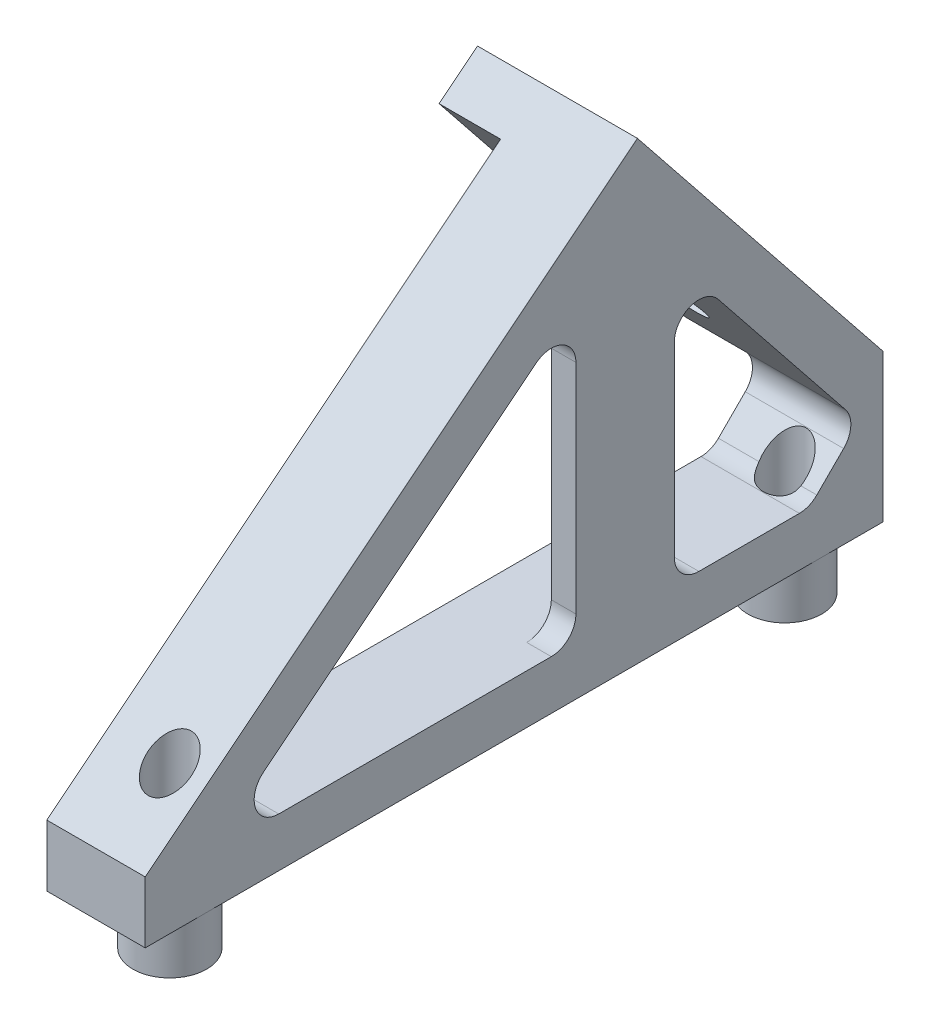
SolidWorks part; units mm, degrees
ref_plane "前基準面" through (0, 0, 0) normal (0, 0, 1) x (1, 0, 0)
ref_plane "上基準面" through (0, 0, 0) normal (0, 1, 0) x (1, 0, 0)
ref_plane "右基準面" through (0, 0, 0) normal (1, 0, 0) x (0, 0, -1)
sketch "草圖4" plane through (0, 0, 0) normal (1, 0, 0) x (0, 0, -1)
  line L0 (0, 0) -> (-60, 0)
  line L1 (-60, 0) -> (-60, 5)
  line L2 (-60, 5) -> (-19.9826, 36.9939)
  line L3 (-19.9826, 36.9939) -> (0, 12)
  line L4 (0, 12) -> (0, 0)
  dimension "D1" = 90
  dimension "D2" = 5
  dimension "D3" = 12
  dimension "D4" = 60
  dimension "D5" = 32
extrude "填料-伸長1" add sketch "草圖4" along normal blind 13
sketch "草圖5" plane through (0, 32.3145, 25.8355) normal (0, 0.7811, 0.6245) x (1, 0, 0)
  line L0 (0, 3.4935) -> (5, 3.4935)
  line L1 (0, 7.4935) -> (0, -43.7413) construction
  line L2 (5, 3.4935) -> (5, -49.0452)
  line L3 (5, -49.0452) -> (0, -49.0452)
  line L4 (0, -49.0452) -> (0, 3.4935)
  line L5 (13, 7.4935) -> (0, 7.4935) construction
  dimension "D1" = 5
  dimension "D2" = 4
extrude "除料-伸長1" cut sketch "草圖5" against normal through all
sketch "草圖6" plane through (13, 0, 0) normal (1, 0, 0) x (0, 0, -1)
  line L0 (-24.9826, 27.8751) -> (-24.9826, 4)
  line L1 (-24.9826, 4) -> (-54.8452, 4)
  line L2 (-54.8452, 4) -> (-24.9826, 27.8751)
  line L3 (-19.9826, 36.9939) -> (-60, 5) construction
  line L4 (-60, 0) -> (0, 0) construction
  line L5 (-16.9826, 26.836) -> (-1.9496, 8.033)
  line L6 (-1.9496, 8.033) -> (-5.9826, 4)
  line L7 (-5.9826, 4) -> (-16.9826, 4)
  line L8 (-16.9826, 4) -> (-16.9826, 26.836)
  line L9 (0, 12) -> (-19.9826, 36.9939) construction
  point P5 (-39.9913, 20.9969)
  dimension "D1" = 8
  dimension "D2" = 4
  dimension "D3" = 4
  dimension "D4" = 4
  dimension "D5" = 3
  dimension "D6" = 11
  dimension "D7" = 135
extrude "除料-伸長2" cut sketch "草圖6" against normal through all
fillet "圓角1" radius 2 7 edges at (9, 4, 16.9826) (9, 4, 5.9826) (9, 8.033, 1.9496) (9, 26.836, 16.9826) (9, 4, 54.8452) (9, 4, 24.9826) (9, 27.8751, 24.9826)
sketch "草圖7" plane through (0, 2.1815, -2.7286) normal (0, -0.6245, 0.7811) x (1, 0, 0)
  line L1 (0, 9.3727) -> (5, 9.3727)
  line L2 (5, 4.3696) -> (5, 9.2812) construction
  line L3 (5, 9.3727) -> (5, 4.3696)
  line L4 (5, 4.3696) -> (0, 4.3696)
  line L5 (0, 4.3696) -> (0, 9.3727) construction
  line L6 (0, 4.3696) -> (0, 9.3727)
extrude "除料-伸長3" cut sketch "草圖7" against normal blind 13
sketch "草圖8" plane through (0, 4.6794, -5.8529) normal (0, 0.6245, -0.7811) x (-1, 0, 0)
  line L0 (-13, 41.3727) -> (0, 41.3727) construction
  line L1 (0, 9.3727) -> (0, 41.3727) construction
  line L2 (-5, 9.3727) -> (0, 9.3727) construction
  circle A0 centre (-4, 34.3727) radius 2
  circle A1 centre (-4, 16.3727) radius 2
  dimension "D3" = 4
  dimension "D4" = 4
  dimension "D5" = 4
  dimension "D6" = 7
  dimension "D1" = 7
  dimension "D2" = 4
extrude "除料-伸長4" cut sketch "草圖8" against normal blind 13
sketch "草圖9" plane through (5, 0, 0) normal (-1, 0, 0) x (0, 0, 1)
  line L0 (23.1069, 34.4961) -> (3.1242, 9.5022) construction
  line L1 (20.609, 31.3718) -> (3.0671, 9.4307)
  line L2 (28.2315, 25.2776) -> (50.3898, 7.5621) construction
  line L3 (20.609, 31.3718) -> (50.3898, 7.5621)
  line L4 (5.3968, 4.5858) -> (3.215, 6.7676) construction
  line L5 (5.3968, 4.5858) -> (3.215, 6.7676)
  line L6 (6.811, 4) -> (49.1409, 4)
  arc A0 (3.0671, 9.4307) -> (3.215, 6.7676) centre (4.6292, 8.1818) ccw construction
  arc A1 (5.3968, 4.5858) -> (6.811, 4) centre (6.811, 6) ccw construction
  arc A2 (49.1409, 4) -> (50.3898, 7.5621) centre (49.1409, 6) ccw construction
  arc A3 (3.0671, 9.4307) -> (3.215, 6.7676) centre (4.6292, 8.1818) ccw
  arc A4 (5.3968, 4.5858) -> (6.811, 4) centre (6.811, 6) ccw
  arc A5 (49.1409, 4) -> (50.3898, 7.5621) centre (49.1409, 6) ccw
extrude "除料-伸長5" cut sketch "草圖9" against normal blind 6
sketch "草圖10" plane through (0, 0, 0) normal (0, -1, 0) x (1, 0, 0)
  line L0 (13, 60) -> (13, 0) construction
  line L1 (13, 60) -> (5, 60) construction
  line L2 (13, 0) -> (5, 0) construction
  circle A0 centre (10, 55) radius 3
  circle A1 centre (10, 5) radius 3
  dimension "D1" = 6
  dimension "D2" = 6
  dimension "D3" = 5
  dimension "D4" = 5
extrude "填料-伸長2" add sketch "草圖10" along normal blind 4
sketch "草圖11" plane through (0, -4, 0) normal (0, -1, 0) x (-1, 0, 0)
  circle A0 centre (-10, -55) radius 1.75
  circle A1 centre (-10, -5) radius 1.75
  dimension "D1" = 3.5
extrude "除料-伸長6" cut sketch "草圖11" against normal up to next
